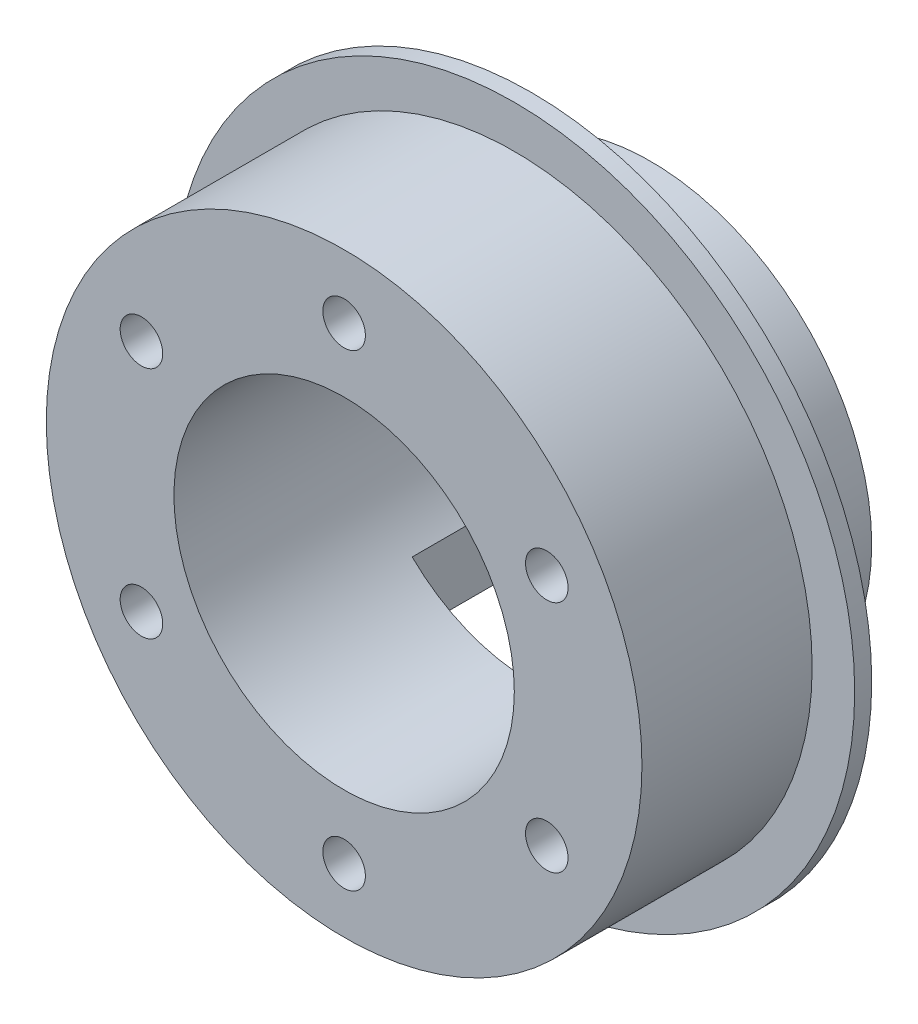
SolidWorks part; units mm, degrees
ref_plane "정면" through (0, 0, 0) normal (0, 0, 1) x (1, 0, 0)
ref_plane "윗면" through (0, 0, 0) normal (0, 1, 0) x (1, 0, 0)
ref_plane "우측면" through (0, 0, 0) normal (1, 0, 0) x (0, 0, -1)
sketch "스케치1" plane through (0, 0, 0) normal (0, 0, 1) x (1, 0, 0)
  circle A0 centre (0, 0) radius 13
  dimension "D1" = 26
extrude "보스-돌출1" add sketch "스케치1" along normal blind 2
sketch "스케치2" plane through (0, 0, 2) normal (0, 0, 1) x (1, 0, 0)
  circle A0 centre (0, 0) radius 13
  circle A1 centre (0, 0) radius 10
  circle A5 centre (0, 0) radius 13 construction
  dimension "D1" = 3
extrude "보스-돌출2" add sketch "스케치2" along normal blind 5
sketch "스케치4" plane through (0, 0, 7) normal (0, 0, 1) x (1, 0, 0)
  circle A0 centre (0, 0) radius 20
  circle A1 centre (0, 0) radius 10
  circle A2 centre (0, 0) radius 10 construction
  dimension "D1" = 40
extrude "보스-돌출3" add sketch "스케치4" along normal blind 1
sketch "스케치5" plane through (0, 0, 8) normal (0, 0, 1) x (1, 0, 0)
  circle A0 centre (0, 0) radius 10
  circle A1 centre (0, 0) radius 17.5
  circle A2 centre (0, 0) radius 10 construction
  dimension "D1" = 35
extrude "보스-돌출4" add sketch "스케치5" along normal blind 10
sketch "스케치6" plane through (0, 0, 18) normal (0, 0, 1) x (1, 0, 0)
  circle A0 centre (0, 0) radius 13.75 construction
  circle A1 centre (11.9078, 6.875) radius 1.25
  circle A2 centre (11.9078, -6.875) radius 1.25
  circle A3 centre (0, -13.75) radius 1.25
  circle A4 centre (-11.9078, -6.875) radius 1.25
  circle A5 centre (-11.9078, 6.875) radius 1.25
  circle A6 centre (0, 0) radius 10 construction
  circle A7 centre (0, 13.75) radius 1.25
  point P20 (0, 0)
  dimension "D1" = 3.75
  dimension "D2" = 2.5
  dimension "D3" = 6
extrude "컷-돌출1" cut sketch "스케치6" against normal blind 8
sketch "스케치7" plane through (0, 0, 0) normal (0, 0, -1) x (-1, 0, 0)
  line L0 (7, 3) -> (-7, 3) construction
  line L1 (7, 3) -> (7, -3) construction
  line L2 (-7, 3) -> (-7, -3) construction
  line L3 (7, -3) -> (-7, -3) construction
  line L4 (7, 3) -> (-7, -3) construction
  line L5 (-7, 3) -> (7, -3) construction
  circle A0 centre (0, 0) radius 7 construction
  circle A5 centre (0, 0) radius 3
  circle A6 centre (0, 0) radius 7 construction
  circle A7 centre (0, 0) radius 7 construction
  circle A8 centre (0, 0) radius 7 construction
  circle A9 centre (0, 7) radius 1
  circle A11 centre (0, -7) radius 1
  circle A13 centre (-7, 3) radius 1
  circle A14 centre (-7, -3) radius 1
  circle A15 centre (7, 3) radius 1
  circle A16 centre (7, -3) radius 1
  point P14 (0, -1.0172)
  dimension "D1" = 14
  dimension "D2" = 2
  dimension "D4" = 6
  dimension "D3" = 6
extrude "컷-돌출2" cut sketch "스케치7" against normal through all
sketch "스케치8" plane through (0, 0, 0) normal (0, 1, 0) x (1, 0, 0)
  line L0 (13, 0) -> (-13, 0) construction
  line L1 (-7, -2) -> (7, -2)
  line L2 (-7, -2) -> (-7, -7)
  line L3 (-7, -7) -> (7, -7)
  line L4 (7, -2) -> (7, -7)
  line L5 (-7, -2) -> (7, -7) construction
  line L6 (-7, -7) -> (7, -2) construction
  line L8 (13, -7) -> (13, 0) construction
  line L9 (-13, 0) -> (-13, -7) construction
  line L10 (13, -7) -> (-13, -7) construction
  point P0 (0, -4.5)
  dimension "D1" = 2
  dimension "D3" = 6
  dimension "D4" = 6
extrude "컷-돌출3" cut sketch "스케치8" against normal through all both and the other way through all
